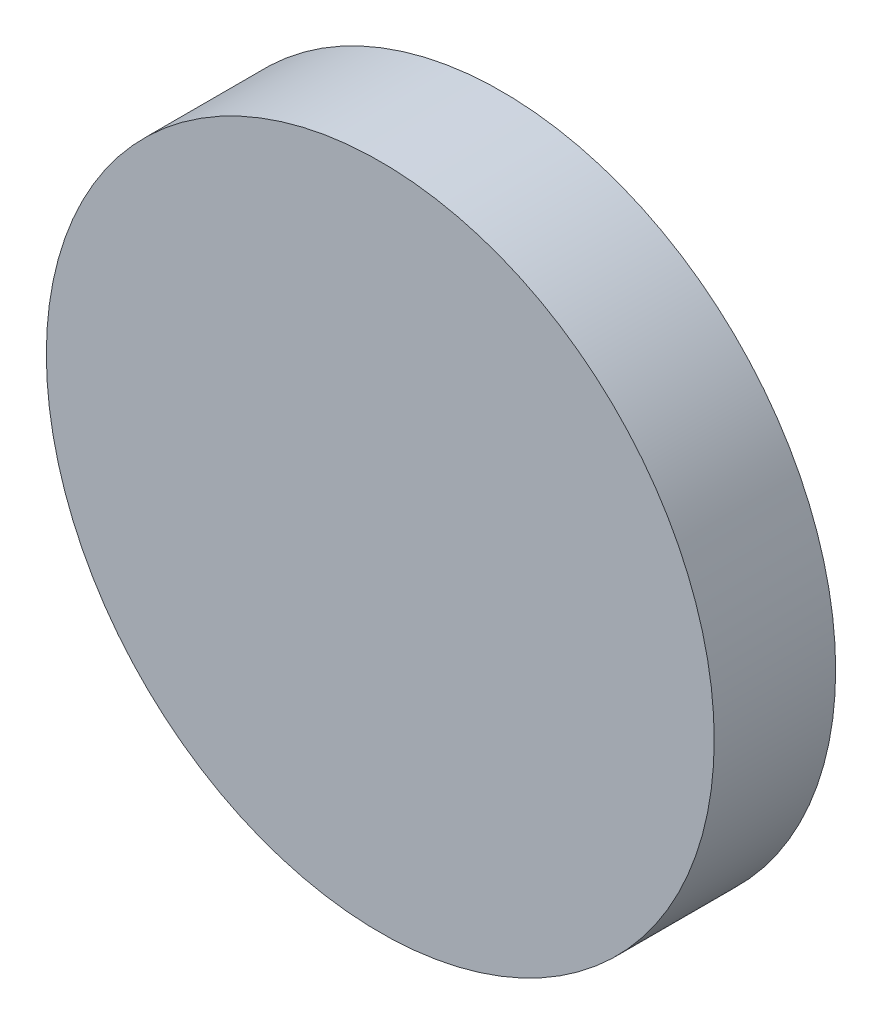
SolidWorks part; units mm, degrees
ref_plane "Front Plane" through (0, 0, 0) normal (0, 0, 1) x (1, 0, 0)
ref_plane "Top Plane" through (0, 0, 0) normal (0, 1, 0) x (1, 0, 0)
ref_plane "Right Plane" through (0, 0, 0) normal (1, 0, 0) x (0, 0, -1)
sketch "Sketch1" plane through (0, 0, 0) normal (0, 0, 1) x (1, 0, 0)
  circle A0 centre (0, 0) radius 209.55
  dimension "D1" = 419.1
extrude "Boss-Extrude1" add sketch "Sketch1" along normal blind 76.2
